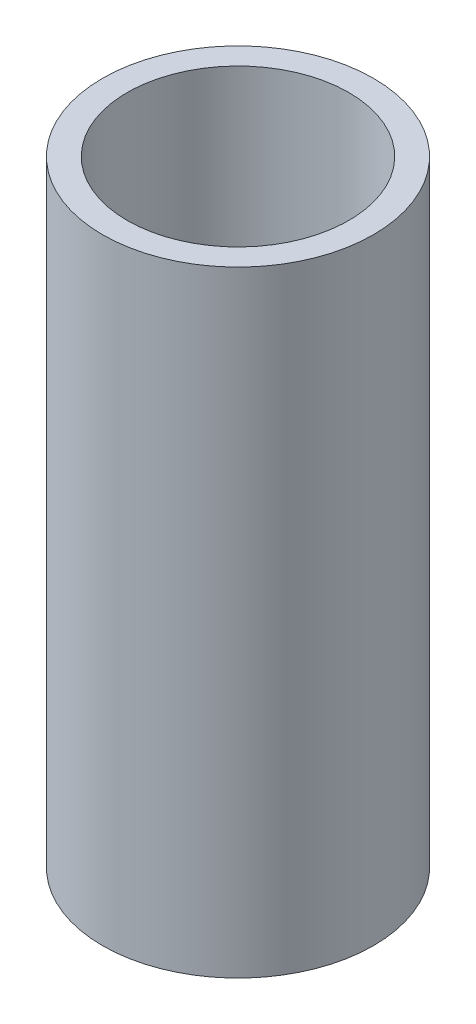
SolidWorks part; units mm, degrees
ref_plane "Front Plane" through (0, 0, 0) normal (0, 0, 1) x (1, 0, 0)
ref_plane "Top Plane" through (0, 0, 0) normal (0, 1, 0) x (1, 0, 0)
ref_plane "Right Plane" through (0, 0, 0) normal (1, 0, 0) x (0, 0, -1)
sketch "Sketch1" plane through (0, 0, 0) normal (0, 1, 0) x (1, 0, 0)
  circle A0 centre (0, 0) radius 9
  circle A1 centre (0, 0) radius 11
  dimension "D1" = 18
  dimension "D2" = 22
extrude "Boss-Extrude1" add sketch "Sketch1" along normal blind 50
